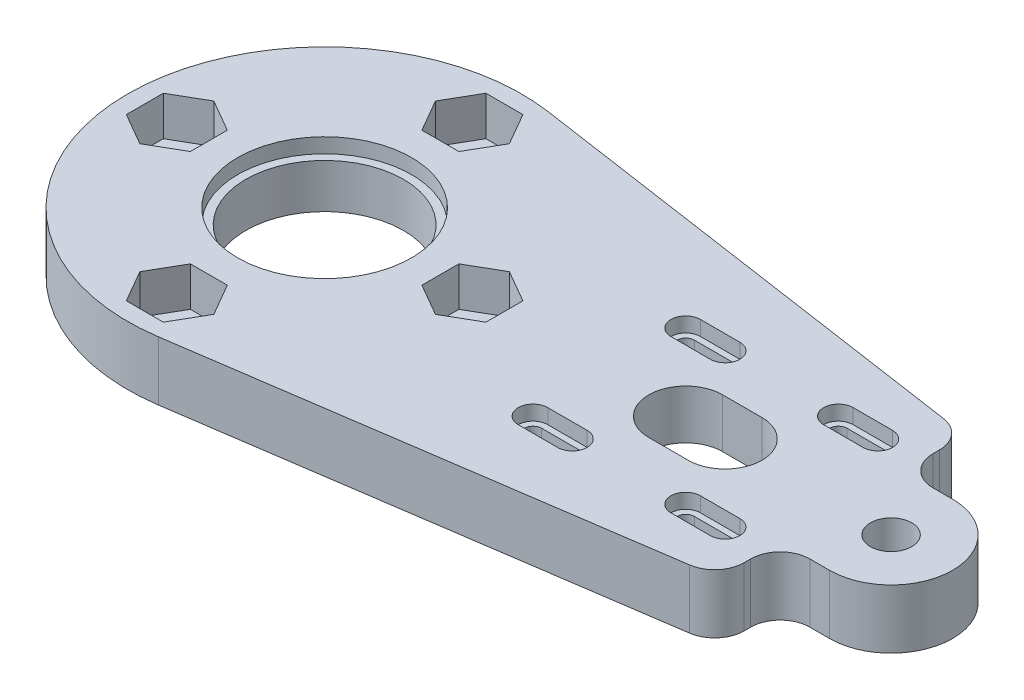
SolidWorks part; units mm, degrees
ref_plane "Front Plane" through (0, 0, 0) normal (0, 0, 1) x (1, 0, 0)
ref_plane "Top Plane" through (0, 0, 0) normal (0, 1, 0) x (1, 0, 0)
ref_plane "Right Plane" through (0, 0, 0) normal (1, 0, 0) x (0, 0, -1)
sketch "Sketch1" plane through (0, 0, 0) normal (0, 1, 0) x (1, 0, 0)
  line L0 (5.8155, 39.575) -> (105, 25)
  line L1 (105, 25) -> (105, -25)
  line L2 (105, -25) -> (5.8155, -39.575)
  arc A0 (5.8155, 39.575) -> (5.8155, -39.575) centre (0, 0) ccw
  circle A1 centre (0, 0) radius 10
  point P4 (105, 0)
  dimension "D1" = 40
  dimension "D4" = 20
  dimension "D2" = 50
  dimension "D3" = 105
extrude "Boss-Extrude1" add sketch "Sketch1" along normal blind 12
sketch "Sketch2" plane through (0, 12, 0) normal (0, 1, 0) x (1, 0, 0)
  circle A0 centre (0, 0) radius 17.65
  dimension "D1" = 35.3
extrude "Cut-Extrude1" cut sketch "Sketch2" against normal blind 3
sketch "Sketch3" plane through (0, 12, 0) normal (0, 1, 0) x (1, 0, 0)
  line L0 (73.3, 0) -> (81.3, 0) construction
  line L1 (73.3, 7.5) -> (81.3, 7.5)
  line L2 (73.3, -7.5) -> (81.3, -7.5)
  arc A0 (73.3, 7.5) -> (73.3, -7.5) centre (73.3, 0) ccw
  arc A1 (81.3, -7.5) -> (81.3, 7.5) centre (81.3, 0) ccw
  point P3 (77.3, 0)
  dimension "D1" = 15
  dimension "D2" = 8
  dimension "D3" = 77.3
extrude "Cut-Extrude2" cut sketch "Sketch3" against normal up to surface (12 mm away) up to face at (43.9539, 0, 0)
sketch "Sketch4" plane through (0, 12, 0) normal (0, 1, 0) x (1, 0, 0)
  circle A0 centre (30, 0) radius 4
  circle A1 centre (0, -30) radius 4
  circle A2 centre (-30, 0) radius 4
  circle A3 centre (0, 30) radius 4
  point P12 (0, 0)
  dimension "D2" = 8
  dimension "D1" = 30
  dimension "D3" = 4
extrude "Cut-Extrude3" cut sketch "Sketch4" against normal up to surface (12 mm away) up to face at (77.3, 0, 0)
sketch "Sketch5" plane through (0, 9, 0) normal (0, -1, 0) x (1, 0, 0)
  circle A0 centre (0, 0) radius 16
  dimension "D1" = 32
extrude "Cut-Extrude4" cut sketch "Sketch5" along normal through all
sketch "Sketch6" plane through (0, 0, 0) normal (0, -1, 0) x (1, 0, 0)
  line L0 (73.3, 7.5) -> (81.3, -7.5) construction
  line L1 (51.8, 21.5) -> (102.8, 21.5)
  line L2 (51.8, 21.5) -> (51.8, -21.5)
  line L3 (51.8, -21.5) -> (102.8, -21.5)
  line L4 (102.8, 21.5) -> (102.8, -21.5)
  line L5 (51.8, 21.5) -> (102.8, -21.5) construction
  line L6 (51.8, -21.5) -> (102.8, 21.5) construction
  point P0 (77.3, 0)
  point P9 (77.3, 0)
  dimension "D1" = 43
  dimension "D2" = 51
extrude "Cut-Extrude5" cut sketch "Sketch6" against normal blind 2
chamfer "Chamfer1" distance 2 angle 45 4 edges at (51.8, 1, 21.5) (102.8, 1, 21.5) (102.8, 1, -21.5) (51.8, 1, -21.5)
sketch "Sketch7" plane through (0, 12, 0) normal (0, 1, 0) x (1, 0, 0)
  line L24 (-7.5056, 30) -> (-3.7528, 23.5)
  line L25 (-30, -7.5056) -> (-23.5, -3.7528)
  line L26 (-23.5, -3.7528) -> (-23.5, 3.7528)
  line L27 (-23.5, 3.7528) -> (-30, 7.5056)
  line L28 (-30, 7.5056) -> (-36.5, 3.7528)
  line L29 (-36.5, 3.7528) -> (-36.5, -3.7528)
  line L30 (-36.5, -3.7528) -> (-30, -7.5056)
  line L31 (-3.7528, 23.5) -> (3.7528, 23.5)
  line L32 (3.7528, 23.5) -> (7.5056, 30)
  line L33 (7.5056, 30) -> (3.7528, 36.5)
  line L34 (3.7528, 36.5) -> (-3.7528, 36.5)
  line L35 (-3.7528, 36.5) -> (-7.5056, 30)
  line L36 (30, 7.5056) -> (23.5, 3.7528)
  line L37 (23.5, 3.7528) -> (23.5, -3.7528)
  line L38 (23.5, -3.7528) -> (30, -7.5056)
  line L39 (30, -7.5056) -> (36.5, -3.7528)
  line L40 (36.5, -3.7528) -> (36.5, 3.7528)
  line L41 (36.5, 3.7528) -> (30, 7.5056)
  line L42 (7.5056, -30) -> (3.7528, -23.5)
  line L43 (3.7528, -23.5) -> (-3.7528, -23.5)
  line L44 (-3.7528, -23.5) -> (-7.5056, -30)
  line L45 (-7.5056, -30) -> (-3.7528, -36.5)
  line L46 (-3.7528, -36.5) -> (3.7528, -36.5)
  line L47 (3.7528, -36.5) -> (7.5056, -30)
  circle A4 centre (-30, 0) radius 6.5 construction
  point P12 (0, 0)
  point P30 (0, 0)
  point P32 (0, 0)
  dimension "D1" = 13
  dimension "D2" = 4
extrude "Cut-Extrude6" cut sketch "Sketch7" against normal blind 8
sketch "Sketch9" plane through (0, 12, 0) normal (0, 1, 0) x (1, 0, 0)
  line L0 (57.8, 15.5) -> (65.8, 15.5) construction
  line L1 (57.8, 18.5) -> (65.8, 18.5)
  line L2 (57.8, 12.5) -> (65.8, 12.5)
  line L3 (88.8, 15.5) -> (96.8, 15.5) construction
  line L4 (88.8, 18.5) -> (96.8, 18.5)
  line L5 (88.8, 12.5) -> (96.8, 12.5)
  line L6 (57.8, -15.5) -> (65.8, -15.5) construction
  line L7 (57.8, -12.5) -> (65.8, -12.5)
  line L8 (57.8, -18.5) -> (65.8, -18.5)
  line L9 (88.8, -15.5) -> (96.8, -15.5) construction
  line L10 (88.8, -12.5) -> (96.8, -12.5)
  line L11 (88.8, -18.5) -> (96.8, -18.5)
  line L12 (61.8, -15.5) -> (92.8, 15.5) construction
  line L13 (61.8, 15.5) -> (92.8, -15.5) construction
  line L14 (73.3, 7.5) -> (81.3, -7.5) construction
  arc A0 (57.8, 18.5) -> (57.8, 12.5) centre (57.8, 15.5) ccw
  arc A1 (65.8, 12.5) -> (65.8, 18.5) centre (65.8, 15.5) ccw
  arc A2 (88.8, 18.5) -> (88.8, 12.5) centre (88.8, 15.5) ccw
  arc A3 (96.8, 12.5) -> (96.8, 18.5) centre (96.8, 15.5) ccw
  arc A4 (57.8, -12.5) -> (57.8, -18.5) centre (57.8, -15.5) ccw
  arc A5 (65.8, -18.5) -> (65.8, -12.5) centre (65.8, -15.5) ccw
  arc A6 (88.8, -12.5) -> (88.8, -18.5) centre (88.8, -15.5) ccw
  arc A7 (96.8, -18.5) -> (96.8, -12.5) centre (96.8, -15.5) ccw
  point P2 (61.8, 15.5)
  point P8 (92.8, 15.5)
  point P15 (61.8, -15.5)
  point P22 (92.8, -15.5)
  point P36 (77.3, 0)
  point P37 (77.3, 0)
  dimension "D1" = 6
  dimension "D2" = 6
  dimension "D3" = 8
  dimension "D4" = 8
  dimension "D5" = 8
  dimension "D6" = 8
  dimension "D7" = 6
  dimension "D8" = 6
  dimension "D9" = 31
  dimension "D10" = 31
extrude "Cut-Extrude7" cut sketch "Sketch9" against normal blind 3
sketch "Sketch10" plane through (0, 9, 0) normal (0, 1, 0) x (1, 0, 0)
  line L4 (57.8, 13.75) -> (65.8, 13.75)
  line L5 (65.8, 17.25) -> (57.8, 17.25)
  line L6 (57.8, 13.75) -> (65.8, 13.75)
  line L7 (65.8, 17.25) -> (57.8, 17.25)
  line L10 (88.8, 13.75) -> (96.8, 13.75)
  line L11 (96.8, 17.25) -> (88.8, 17.25)
  line L12 (88.8, 13.75) -> (96.8, 13.75)
  line L13 (96.8, 17.25) -> (88.8, 17.25)
  line L16 (57.8, -17.25) -> (65.8, -17.25)
  line L17 (65.8, -13.75) -> (57.8, -13.75)
  line L18 (57.8, -17.25) -> (65.8, -17.25)
  line L19 (65.8, -13.75) -> (57.8, -13.75)
  line L22 (88.8, -17.25) -> (96.8, -17.25)
  line L23 (96.8, -13.75) -> (88.8, -13.75)
  line L24 (88.8, -17.25) -> (96.8, -17.25)
  line L25 (96.8, -13.75) -> (88.8, -13.75)
  arc A2 (96.8, 13.75) -> (96.8, 17.25) centre (96.8, 15.5) ccw
  arc A3 (96.8, 13.75) -> (96.8, 17.25) centre (96.8, 15.5) ccw
  arc A4 (57.8, 17.25) -> (57.8, 13.75) centre (57.8, 15.5) ccw
  arc A5 (65.8, 13.75) -> (65.8, 17.25) centre (65.8, 15.5) ccw
  arc A6 (57.8, 17.25) -> (57.8, 13.75) centre (57.8, 15.5) ccw
  arc A7 (65.8, 13.75) -> (65.8, 17.25) centre (65.8, 15.5) ccw
  arc A8 (96.8, -17.25) -> (96.8, -13.75) centre (96.8, -15.5) ccw
  arc A9 (96.8, -17.25) -> (96.8, -13.75) centre (96.8, -15.5) ccw
  arc A10 (88.8, 17.25) -> (88.8, 13.75) centre (88.8, 15.5) ccw
  arc A12 (88.8, 17.25) -> (88.8, 13.75) centre (88.8, 15.5) ccw
  arc A16 (57.8, -13.75) -> (57.8, -17.25) centre (57.8, -15.5) ccw
  arc A17 (65.8, -17.25) -> (65.8, -13.75) centre (65.8, -15.5) ccw
  arc A18 (57.8, -13.75) -> (57.8, -17.25) centre (57.8, -15.5) ccw
  arc A19 (65.8, -17.25) -> (65.8, -13.75) centre (65.8, -15.5) ccw
  arc A22 (88.8, -13.75) -> (88.8, -17.25) centre (88.8, -15.5) ccw
  arc A24 (88.8, -13.75) -> (88.8, -17.25) centre (88.8, -15.5) ccw
  dimension "D2" = 1.25
  dimension "D1" = 1.25
  dimension "D3" = 1.25
  dimension "D4" = 1.25
extrude "Cut-Extrude8" cut sketch "Sketch10" against normal up to surface (7 mm away) up to face at (77.3, 2, 0)
sketch "Sketch11" plane through (0, 12, 0) normal (0, 1, 0) x (1, 0, 0)
  line L0 (105, -12.5) -> (105, 12.5)
  line L1 (105, -25) -> (105, 25) construction
  line L2 (105, 12.5) -> (115, 12.5)
  line L3 (115, -12.5) -> (105, -12.5)
  arc A0 (115, 12.5) -> (115, -12.5) centre (115, 0) cw
  circle A1 centre (115, 0) radius 4.2
  point P7 (105, 0)
  point P8 (105, 0)
  dimension "D1" = 25
  dimension "D3" = 8.4
  dimension "D2" = 10
extrude "Boss-Extrude2" add sketch "Sketch11" against normal up to surface (12 mm away) up to face at (77.3, 0, 0)
fillet "Fillet1" radius 6 4 edges at (105, 6, -12.5) (105, 6, -25) (105, 6, 25) (105, 6, 12.5)
